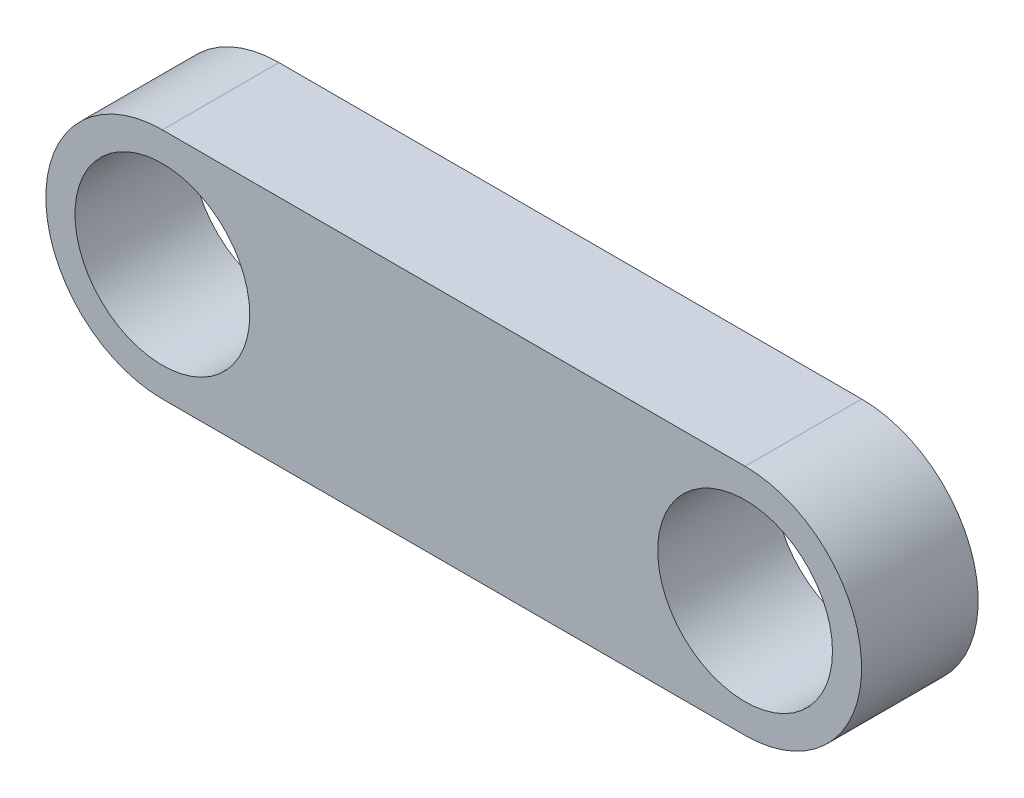
SolidWorks part; units mm, degrees
ref_plane "Front Plane" through (0, 0, 0) normal (0, 0, 1) x (1, 0, 0)
ref_plane "Top Plane" through (0, 0, 0) normal (0, 1, 0) x (1, 0, 0)
ref_plane "Right Plane" through (0, 0, 0) normal (1, 0, 0) x (0, 0, -1)
sketch "Sketch1" plane through (0, 0, 0) normal (0, 0, 1) x (1, 0, 0)
  line L0 (-15.4652, -13.3411) -> (-5.4652, -13.3411)
  line L1 (-15.4652, -9.3411) -> (-5.4652, -9.3411)
  arc A0 (-15.4652, -13.3411) -> (-15.4652, -9.3411) centre (-15.4652, -11.3411) cw
  arc A1 (-5.4652, -9.3411) -> (-5.4652, -13.3411) centre (-5.4652, -11.3411) cw
  circle A2 centre (-15.4652, -11.3411) radius 1.5
  circle A3 centre (-5.4652, -11.3411) radius 1.5
  dimension "D1" = 2
extrude "Boss-Extrude1" add sketch "Sketch1" along normal blind 2
